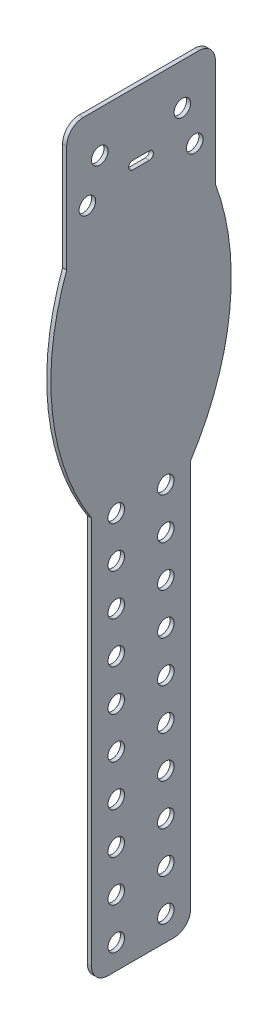
SolidWorks part; units mm, degrees
material "PVC 0.007 Plasticized"
ref_plane "Front Plane" through (0, 0, 0) normal (0, 0, 1) x (1, 0, 0)
ref_plane "Top Plane" through (0, 0, 0) normal (0, 1, 0) x (1, 0, 0)
ref_plane "Right Plane" through (0, 0, 0) normal (1, 0, 0) x (0, 0, -1)
sketch "Sketch1" plane through (0, 0, 0) normal (1, 0, 0) x (0, 0, -1)
  line L0 (12, -183) -> (12, -85)
  line L1 (-18, 0) -> (18, 0)
  line L2 (-18, 0) -> (-18, -183) construction
  line L3 (-18, -183) -> (18, -183) construction
  line L4 (18, 0) -> (18, -183) construction
  line L5 (-18, 0) -> (18, -183) construction
  line L6 (-18, -183) -> (18, 0) construction
  line L7 (-12, -183) -> (-12, -85)
  line L8 (12, -85) -> (-12, -85) construction
  line L9 (18, -30) -> (-18, -30) construction
  line L10 (18, 0) -> (18, -30)
  line L11 (-18, 0) -> (-18, -30)
  line L12 (-21.8408, -51.4826) -> (21.8408, -51.4826) construction
  line L13 (12, -183) -> (-12, -183)
  arc A0 (18, -30) -> (12, -85) centre (-40.1592, -51.4826) cw
  arc A1 (-18, -30) -> (-12, -85) centre (40.1592, -51.4826) ccw
  point P4 (0, -91.5)
  point P5 (0, 0)
  point P10 (0, -85)
  dimension "D6" = 62
  dimension "D7" = 62
  dimension "D1" = 30
  dimension "D2" = 36
  dimension "D3" = 24
  dimension "D4" = 183
  dimension "D5" = 55
  dimension "D8" = 43.6815
extrude "Boss-Extrude1" add sketch "Sketch1" along normal blind 1 contours L1 L10 A0 L0 L13 L7 A1 L11
hole_wizard "Ø4.0 (4) Diameter Hole3" positions "Sketch6" profile "Sketch7" hole size "Ø4.0" standard "ISO" end condition through all
sketch "Sketch6" plane through (0, 0, 0) normal (-1, 0, 0) x (0, 0, 1)
  point P0 (10, -10)
  point P3 (-10, -10)
sketch "Sketch7" plane through (0, -10, 10) normal (0, 1, 0) x (0, 0, 1)
  line L0 (0, 0) -> (0, 1)
  line L1 (0, 1) -> (2, 1)
  line L2 (2, 1) -> (2, 0)
  line L5 (2, 0) -> (0, 0)
  line L11 (0, -6.35) -> (0, 107.95) construction
  dimension "Thru Hole Dia." = 4
  dimension "Thru Hole Depth" = 1
hole_wizard "Ø4.0 (4) Diameter Hole2" positions "Sketch8" profile "Sketch9" hole size "Ø4.0" standard "ISO" end condition through all
sketch "Sketch8" plane through (0, 0, 0) normal (-1, 0, 0) x (0, 0, 1)
  point P4 (-13, -19)
  point P7 (13, -19)
sketch "Sketch9" plane through (0, -19, -13) normal (0, 1, 0) x (0, 0, 1)
  line L0 (0, 0) -> (0, 1)
  line L1 (0, 1) -> (2, 1)
  line L2 (2, 1) -> (2, 0)
  line L5 (2, 0) -> (0, 0)
  line L11 (0, -6.35) -> (0, 107.95) construction
  dimension "Thru Hole Dia." = 4
  dimension "Thru Hole Depth" = 1
sketch "Sketch10" plane through (1, 0, 0) normal (1, 0, 0) x (0, 0, -1)
  line L0 (-2, -16) -> (2, -16) construction
  line L1 (-2, -15) -> (2, -15)
  line L2 (-2, -17) -> (2, -17)
  line L3 (-18, 0) -> (18, 0) construction
  arc A0 (-2, -15) -> (-2, -17) centre (-2, -16) ccw
  arc A1 (2, -17) -> (2, -15) centre (2, -16) ccw
  point P2 (0, -16)
  dimension "D2" = 1
  dimension "D1" = 4
  dimension "D3" = 16
extrude "Cut-Extrude1" cut sketch "Sketch10" against normal through all
hole_wizard "Ø4.0 (4) Diameter Hole1" positions "Sketch12" profile "Sketch11" hole size "Ø4.0" standard "ISO" end condition through all
sketch "Sketch12" plane through (1, 0, 0) normal (1, 0, 0) x (0, 0, -1)
  line L1 (12, -183) -> (-12, -183) construction
  point P0 (-6, -177)
  point P2 (6, -177)
  dimension "D1" = 12
  dimension "D2" = 6
  dimension "D3" = 6
sketch "Sketch11" plane through (1, -177, 6) normal (0, 1, 0) x (0, 0, -1)
  line L0 (0, 0) -> (0, 1)
  line L1 (0, 1) -> (2, 1)
  line L2 (2, 1) -> (2, 0)
  line L5 (2, 0) -> (0, 0)
  line L11 (0, -6.35) -> (0, 107.95) construction
  dimension "Thru Hole Dia." = 4
  dimension "Thru Hole Depth" = 1
pattern_linear "LPattern1" count 10 spacing 10 along (0, 1, 0) of "Ø4.0 (4) Diameter Hole1"
fillet "Fillet1" radius 4 4 edges at (0.5, -183, -12) (0.5, -183, 12) (0.5, 0, 18) (0.5, 0, -18)
